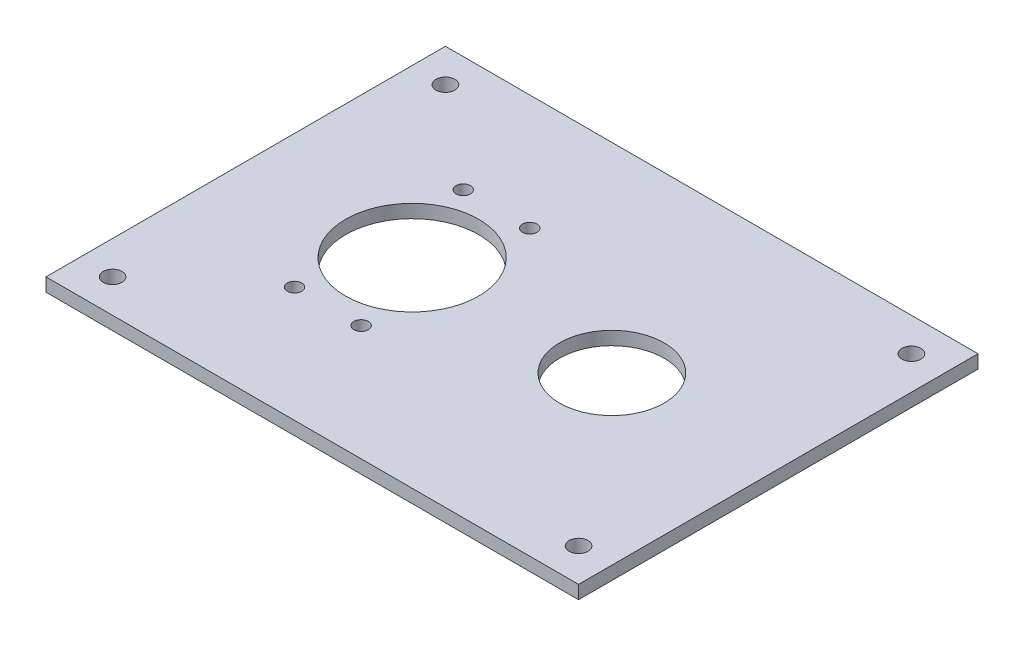
SolidWorks part; units mm, degrees
ref_plane "Front Plane" through (0, 0, 0) normal (0, 0, 1) x (1, 0, 0)
ref_plane "Top Plane" through (0, 0, 0) normal (0, 1, 0) x (1, 0, 0)
ref_plane "Right Plane" through (0, 0, 0) normal (1, 0, 0) x (0, 0, -1)
sketch "Sketch1" plane through (0, 0, 0) normal (0, 1, 0) x (1, 0, 0)
  line L1 (-120, -90) -> (120, -90)
  line L2 (-120, -90) -> (-120, 90)
  line L3 (-120, 90) -> (120, 90)
  line L4 (120, -90) -> (120, 90)
  circle A0 centre (45, 0) radius 23.55
  circle A1 centre (-45, 0) radius 30
  circle A2 centre (-105, -75) radius 4.25
  circle A3 centre (105, -75) radius 4.25
  circle A4 centre (-105, 75) radius 4.25
  circle A5 centre (105, 75) radius 4.25
  circle A6 centre (-60, -38) radius 3.25
  circle A7 centre (-60, 38) radius 3.25
  circle A8 centre (-30, -38) radius 3.25
  circle A9 centre (-30, 38) radius 3.25
extrude "Plate_Extrude" add sketch "Sketch1" along normal blind 6
equation "\"ValveDiameter\" = 50mm"
equation "\"MotorGearTeeth\" = 40"
equation "\"OutputGearTeeth\" = 80"
equation "\"GearModule\" = 1.5mm"
equation "\"PressureAngle\" = 20deg"
equation "\"GearCenterDistance\" = 90mm"
equation "\"GearWidth\" = 18mm"
equation "\"OutputShaftDiameter\" = 20mm"
equation "\"BearingOD\" = 47mm"
equation "\"BearingWidth\" = 14mm"
equation "\"PlateThickness\" = 6mm"
equation "\"ValveRotation\" = 90deg"
